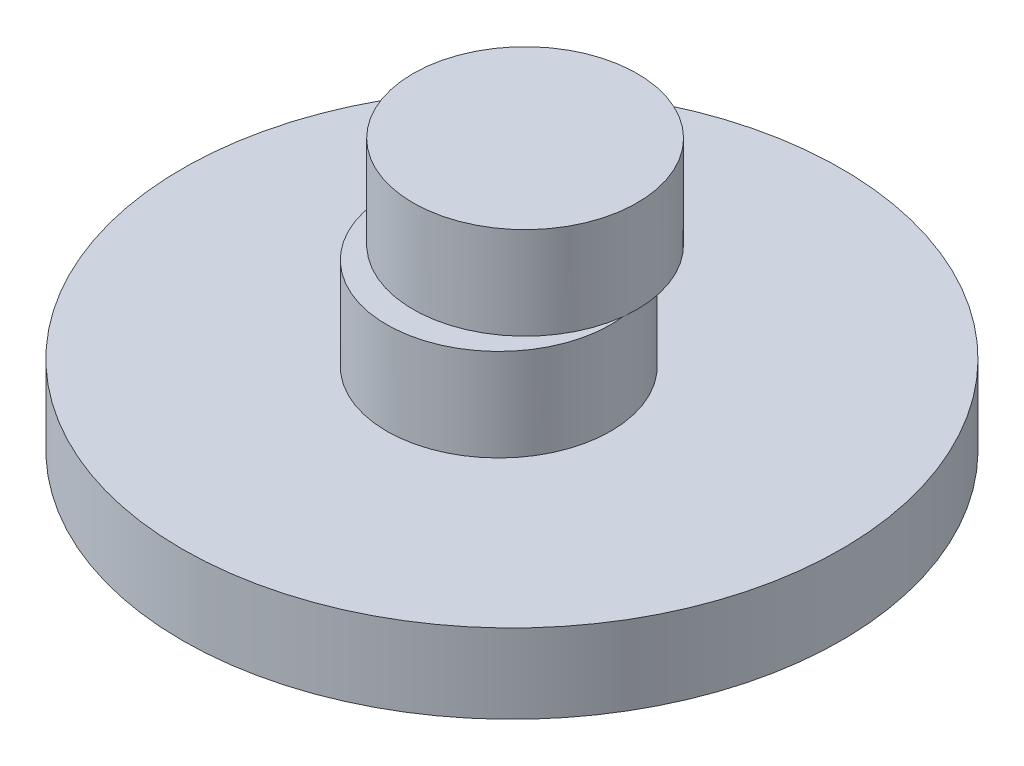
SolidWorks part; units mm, degrees
ref_plane "Front Plane" through (0, 0, 0) normal (0, 0, 1) x (1, 0, 0)
ref_plane "Top Plane" through (0, 0, 0) normal (0, 1, 0) x (1, 0, 0)
ref_plane "Right Plane" through (0, 0, 0) normal (1, 0, 0) x (0, 0, -1)
sketch "Sketch1" plane through (0, 0, 0) normal (0, 1, 0) x (1, 0, 0)
  circle A0 centre (0, 0) radius 8.5
  circle A1 centre (0, 0) radius 4
  dimension "D1" = 17
  dimension "D2" = 8
extrude "Boss-Extrude1" add sketch "Sketch1" along normal blind 7
sketch "Sketch3" plane through (0, 7, 0) normal (0, 1, 0) x (1, 0, 0)
  circle A0 centre (0, 0) radius 4 construction
  circle A1 centre (0, 0) radius 4
  circle A2 centre (0, 0) radius 25
  dimension "D1" = 50
extrude "Boss-Extrude3" add sketch "Sketch3" along normal blind 6
sketch "Sketch4" plane through (0, 13, 0) normal (0, 1, 0) x (1, 0, 0)
  line L0 (0, 0) -> (0, -1) construction
  circle A0 centre (0, -1) radius 8.5
  circle A1 centre (0, 0) radius 4 construction
  circle A2 centre (0, 0) radius 4
  dimension "D2" = 17
  dimension "D1" = 1
extrude "Boss-Extrude4" add sketch "Sketch4" along normal blind 7
sketch "Sketch5" plane through (0, 20, 0) normal (0, 1, 0) x (1, 0, 0)
  line L0 (0, 0) -> (0, 1) construction
  circle A0 centre (0, 0) radius 4 construction
  circle A1 centre (0, 0) radius 4
  circle A2 centre (0, 1) radius 8.5
  dimension "D2" = 17
  dimension "D1" = 1
extrude "Boss-Extrude5" add sketch "Sketch5" along normal blind 7
sketch "Sketch6" plane through (0, 27, 0) normal (0, 1, 0) x (1, 0, 0)
  circle A1 centre (0, 1) radius 8.5
  circle A2 centre (0, 1) radius 8.5
  dimension "D1" = 0
extrude "Boss-Extrude6" add sketch "Sketch6" against normal blind 3
